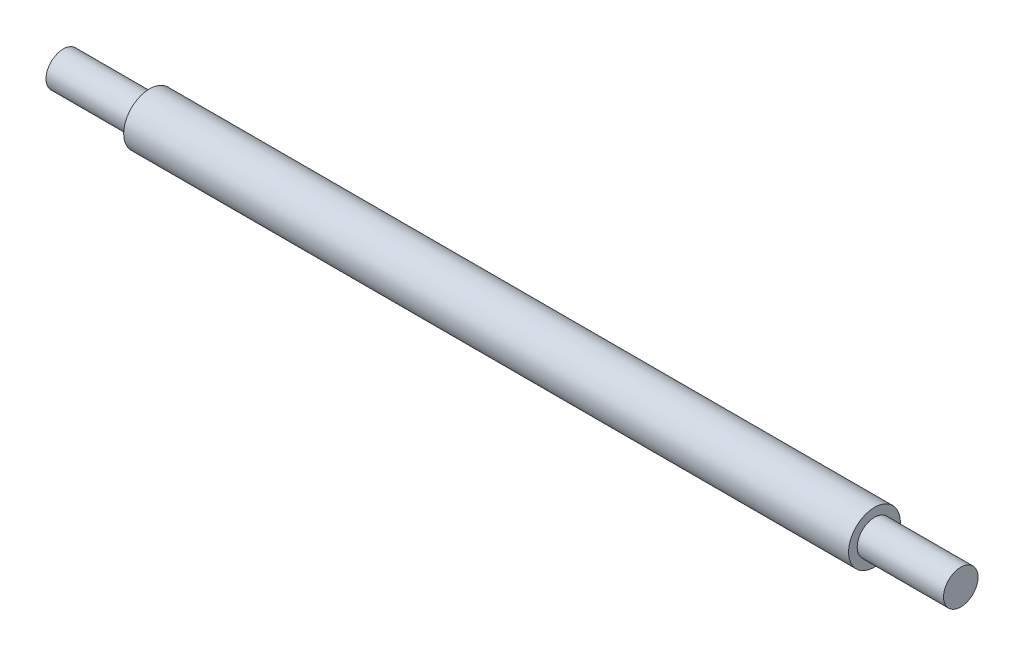
SolidWorks part; units mm, degrees
ref_plane "Front Plane" through (0, 0, 0) normal (0, 0, 1) x (1, 0, 0)
ref_plane "Top Plane" through (0, 0, 0) normal (0, 1, 0) x (1, 0, 0)
ref_plane "Right Plane" through (0, 0, 0) normal (1, 0, 0) x (0, 0, -1)
sketch "Sketch1" plane through (0, 0, 0) normal (0, 0, 1) x (1, 0, 0)
  line L0 (0, 0) -> (104, 0)
  line L1 (0, 0) -> (0, 2)
  line L2 (0, 2) -> (10, 2)
  line L3 (10, 2) -> (10, 3)
  line L4 (104, 0) -> (104, 2)
  line L5 (104, 2) -> (94, 2)
  line L6 (10, 3) -> (94, 3)
  line L7 (94, 3) -> (94, 2)
  dimension "D1" = 104
  dimension "D2" = 2
  dimension "D3" = 10
  dimension "D4" = 3
  dimension "D5" = 2
revolve "Revolve1" add sketch "Sketch1" angle 360 about L0
